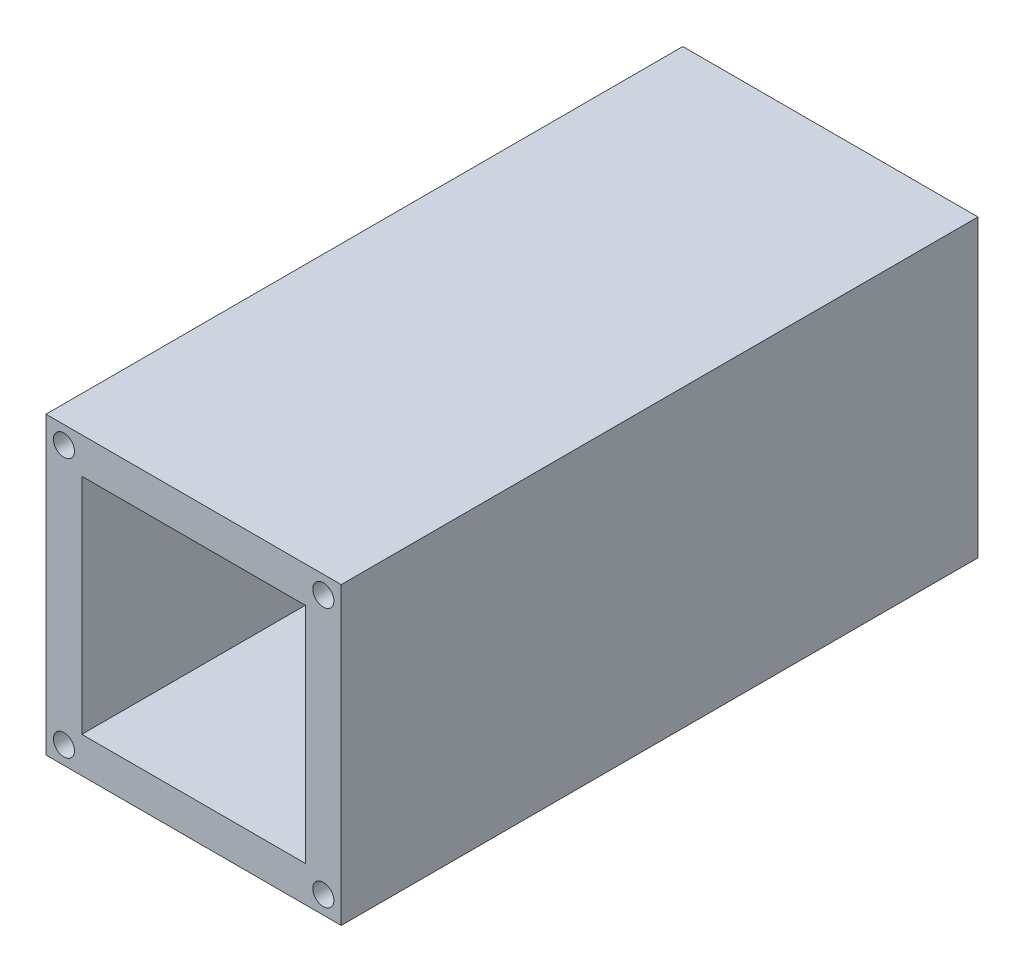
SolidWorks part; units mm, degrees
ref_plane "Alzado" through (0, 0, 0) normal (0, 0, 1) x (1, 0, 0)
ref_plane "Planta" through (0, 0, 0) normal (0, 1, 0) x (1, 0, 0)
ref_plane "Vista lateral" through (0, 0, 0) normal (1, 0, 0) x (0, 0, -1)
sketch "Croquis1" plane through (0, 0, 0) normal (0, 0, 1) x (1, 0, 0)
  line L1 (17.5, -17.5) -> (-17.5, -17.5)
  line L2 (17.5, -17.5) -> (17.5, 17.5)
  line L3 (17.5, 17.5) -> (-17.5, 17.5)
  line L4 (-17.5, -17.5) -> (-17.5, 17.5)
  line L5 (17.5, -17.5) -> (-17.5, 17.5) construction
  line L6 (17.5, 17.5) -> (-17.5, -17.5) construction
  line L11 (10.75, -10.75) -> (-15.75, 15.75) construction
  point P0 (0, 0)
  point P5 (0, 0)
  dimension "D1" = 35
extrude "Saliente-Extruir2" add sketch "Croquis1" along normal blind 75.5
sketch "Croquis2" plane through (0, 0, 75.5) normal (0, 0, 1) x (1, 0, 0)
  line L1 (13.25, -13.25) -> (-13.25, -13.25)
  line L2 (13.25, -13.25) -> (13.25, 13.25)
  line L3 (13.25, 13.25) -> (-13.25, 13.25)
  line L4 (-13.25, -13.25) -> (-13.25, 13.25)
  line L5 (13.25, -13.25) -> (-13.25, 13.25) construction
  line L6 (13.25, 13.25) -> (-13.25, -13.25) construction
  point P0 (0, 0)
  dimension "D1" = 26.5
extrude "Cortar-Extruir1" cut sketch "Croquis2" against normal blind 80
sketch "Croquis4" plane through (0, 0, 75.5) normal (0, 0, 1) x (1, 0, 0)
  circle A0 centre (-15.375, 15.38) radius 1.25
  circle A1 centre (15.38, 15.38) radius 1.25
  circle A2 centre (15.38, -15.38) radius 1.25
  circle A3 centre (-15.375, -15.38) radius 1.25
  dimension "D3" = 2.5
  dimension "D5" = 2.5
  dimension "D7" = 2.5
  dimension "D8" = 2.5
extrude "Cortar-Extruir2" cut sketch "Croquis4" against normal blind 10
sketch "Croquis6" plane through (0, 0, 7) normal (0, 0, 1) x (1, 0, 0)
  line L1 (13.25, -13.25) -> (-13.25, -13.25)
  line L2 (13.25, -13.25) -> (13.25, 13.25)
  line L3 (13.25, 13.25) -> (-13.25, 13.25)
  line L4 (-13.25, -13.25) -> (-13.25, 13.25)
  line L5 (13.25, -13.25) -> (-13.25, 13.25) construction
  line L6 (13.25, 13.25) -> (-13.25, -13.25) construction
  point P0 (0, 0)
extrude "Saliente-Extruir3" add sketch "Croquis6" along normal blind 30
sketch "Croquis7" plane through (0, 0, 37) normal (0, 0, 1) x (1, 0, 0)
  line L0 (13.25, -5) -> (13.25, 5)
  line L1 (13.25, -5) -> (8.3855, -9.27)
  line L2 (13.25, -13.25) -> (13.25, 13.25) construction
  line L3 (-13.25, -5) -> (-13.25, 5)
  line L4 (13.25, 5) -> (8.3855, 9.27)
  line L5 (-13.25, 13.25) -> (-13.25, -13.25) construction
  line L6 (-13.25, 5) -> (-8.3855, 9.27)
  line L7 (-13.25, -5) -> (-8.3855, -9.27)
  arc A1 (-8.3855, 9.27) -> (8.3855, 9.27) centre (0, -0.283) cw
  arc A2 (8.3855, -9.27) -> (-8.3855, -9.27) centre (0, 0.283) cw
  point P6 (13.25, 0)
  point P11 (-13.25, 0)
extrude "Cortar-Extruir3" cut sketch "Croquis7" against normal blind 27
sketch "Croquis8" plane through (0, 0, 7) normal (0, 0, -1) x (-1, 0, 0)
  line L1 (13.25, -13.25) -> (-13.25, -13.25)
  line L2 (13.25, -13.25) -> (13.25, 13.25)
  line L3 (13.25, 13.25) -> (-13.25, 13.25)
  line L4 (-13.25, -13.25) -> (-13.25, 13.25)
  line L5 (13.25, -13.25) -> (-13.25, 13.25) construction
  line L6 (13.25, 13.25) -> (-13.25, -13.25) construction
  point P0 (0, 0)
extrude "Cortar-Extruir4" cut sketch "Croquis8" against normal blind 23
sketch "Croquis9" plane through (0, 0, 0) normal (0, 0, -1) x (-1, 0, 0)
  circle A0 centre (-15.38, 15.38) radius 1.25
  circle A1 centre (15.38, 15.38) radius 1.25
  circle A2 centre (15.38, -15.38) radius 1.25
  circle A3 centre (-15.38, -15.38) radius 1.25
  dimension "D3" = 2.5
  dimension "D5" = 2.5
  dimension "D7" = 2.5
  dimension "D8" = 2.5
extrude "Cortar-Extruir5" cut sketch "Croquis9" against normal blind 10
